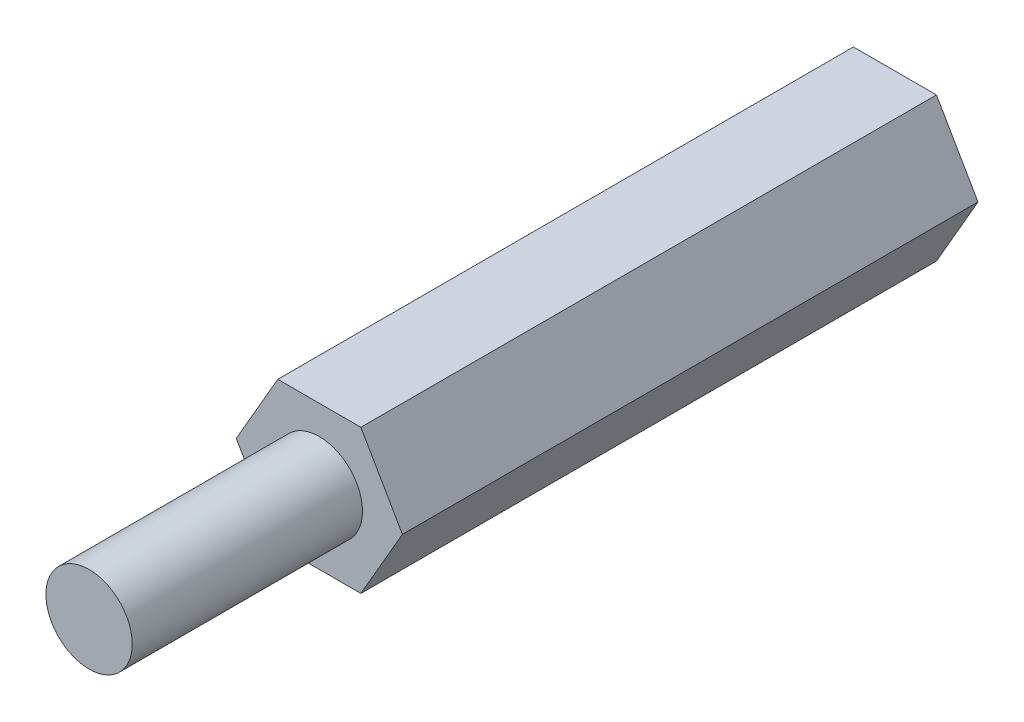
SolidWorks part; units mm, degrees
ref_plane "前视基准面" through (0, 0, 0) normal (0, 0, 1) x (1, 0, 0)
ref_plane "上视基准面" through (0, 0, 0) normal (0, 1, 0) x (1, 0, 0)
ref_plane "右视基准面" through (0, 0, 0) normal (1, 0, 0) x (0, 0, -1)
sketch "草图1" plane through (0, 0, 0) normal (0, 0, 1) x (1, 0, 0)
  line L0 (-28.6627, 0) -> (33.6774, 0) construction
  line L1 (1.4434, -2.5) -> (2.8868, 0)
  line L2 (2.8868, 0) -> (1.4434, 2.5)
  line L3 (1.4434, 2.5) -> (-1.4434, 2.5)
  line L4 (-1.4434, 2.5) -> (-2.8868, 0)
  line L5 (-2.8868, 0) -> (-1.4434, -2.5)
  line L6 (-1.4434, -2.5) -> (1.4434, -2.5)
  circle A0 centre (0, 0) radius 2.5 construction
  dimension "D1" = 5
extrude "拉伸1" add sketch "草图1" along normal blind 20
sketch "草图2" plane through (0, 0, 20) normal (0, 0, 1) x (1, 0, 0)
  circle A0 centre (0, 0) radius 1.5
  dimension "D1" = 3
extrude "拉伸2" add sketch "草图2" along normal blind 8
hole_wizard "M3x0.5 螺纹孔1" positions "3D草图2" profile "草图5" tap size "M3x0.5" standard "ISO"
sketch3d "3D草图2"
  point P0 (0, 0, 0)
  point P2 (0, 0, 0)
  point P3 (0, 0, 0)
  point P4 (0, 0, 0)
sketch "草图5" plane through (0, 0, 0) normal (1, 0, 0) x (0, 1, 0)
  line L0 (0, 0) -> (0, 11.7511)
  line L1 (0, 11.7511) -> (1.25, 11)
  line L2 (1.25, 11) -> (1.25, 0)
  line L5 (1.25, 0) -> (0, 0)
  line L10 (0, 11.7511) -> (-1.25, 11) construction
  line L11 (0, -6.35) -> (0, 107.95) construction
  dimension "蹟恇謂郰芛眻噤" = 2.5
  dimension "蹟恇謂郰芛旮僅" = 11
  dimension "絳芛褒僅" = 118
cosmetic thread "孔螺蚊线1" parameters "D1"=6, "D2"=3
cosmetic thread "孔螺蚊线2" parameters "D1"=6, "D2"=3
cosmetic thread "孔螺蚊线3" parameters "D1"=6, "D2"=3
cosmetic thread "孔螺蚊线4" parameters "D1"=6, "D2"=3
